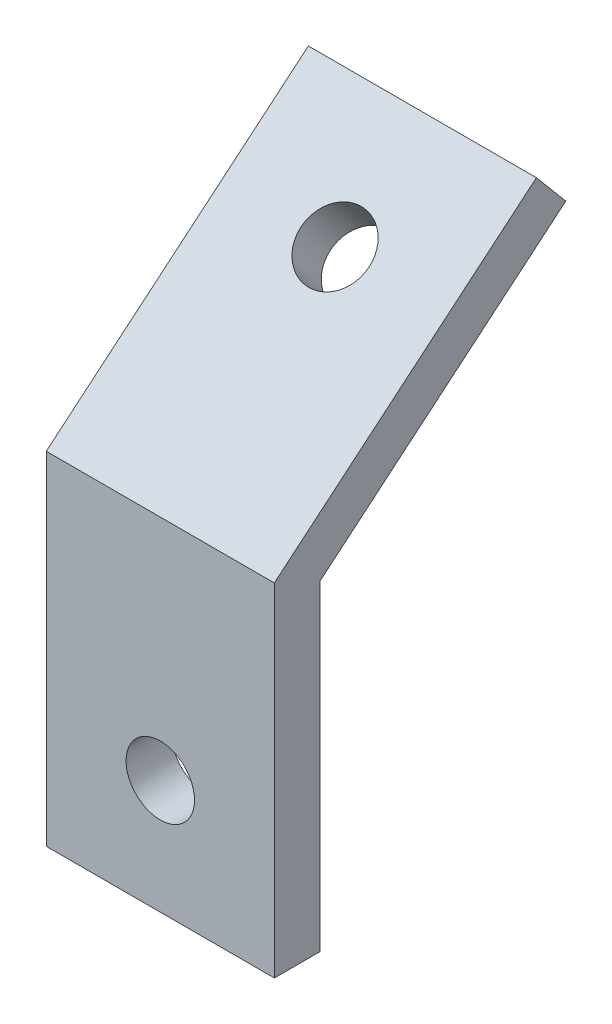
SolidWorks part; units mm, degrees
material "6061 Alloy"
ref_plane "Front Plane" through (0, 0, 0) normal (0, 0, 1) x (1, 0, 0)
ref_plane "Top Plane" through (0, 0, 0) normal (0, 1, 0) x (1, 0, 0)
ref_plane "Right Plane" through (0, 0, 0) normal (1, 0, 0) x (0, 0, -1)
sketch "Sketch1" plane through (0, 0, 0) normal (1, 0, 0) x (0, 0, -1)
  line L0 (0, 0) -> (0, 15)
  line L1 (0, 15) -> (11.4907, 24.6418)
  line L2 (11.4907, 24.6418) -> (12.7762, 23.1097)
  line L3 (12.7762, 23.1097) -> (2, 14.0674)
  line L4 (2, 14.0674) -> (2, 0)
  line L5 (55, 0) -> (-55, 0) construction
  line L6 (2, 0) -> (0, 0)
  line L7 (0, 55) -> (0, -55) construction
  dimension "D1" = 230
  dimension "D2" = 15
  dimension "D3" = 15
  dimension "D4" = 2
  dimension "D5" = 2
extrude "Boss-Extrude1" add sketch "Sketch1" along normal blind 10
sketch "Sketch2" plane through (0, 0, 0) normal (0, 0, 1) x (1, 0, 0)
  line L0 (10, 15) -> (10, 0) construction
  line L1 (5.5, 0) -> (-5.5, 0) construction
  circle A0 centre (5, 5) radius 1.5
  dimension "D1" = 3
  dimension "D2" = 5
  dimension "D3" = 5
extrude "Cut-Extrude1" cut sketch "Sketch2" against normal blind 10
sketch "Sketch4" plane through (0, 8.8024, 7.3861) normal (0, 0.766, 0.6428) x (1, 0, 0)
  line L0 (10, 24.6418) -> (10, 9.6418) construction
  line L1 (10, 24.6418) -> (0, 24.6418) construction
  circle A0 centre (5, 19.6418) radius 1.5
  dimension "D1" = 3
  dimension "D2" = 5
  dimension "D3" = 5
extrude "Cut-Extrude2" cut sketch "Sketch4" against normal blind 10
